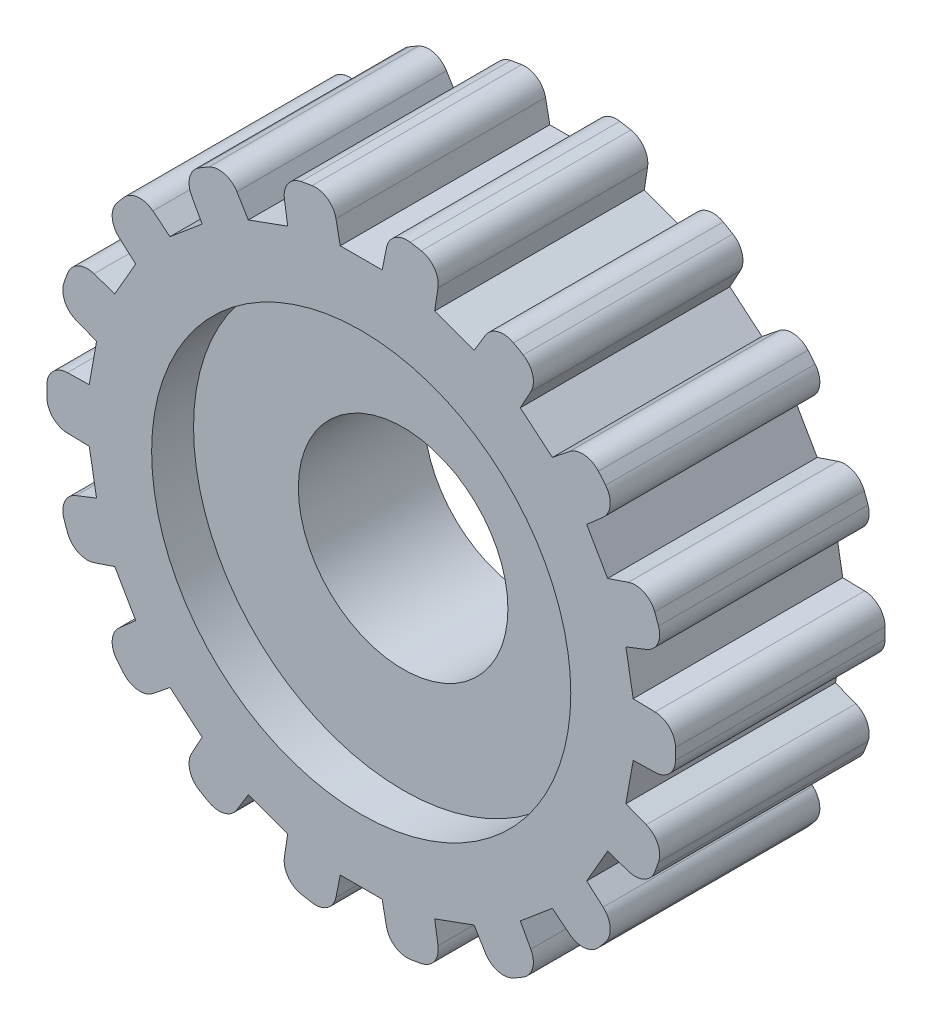
SolidWorks part; units mm, degrees
ref_plane "Front Plane" through (0, 0, 0) normal (0, 0, 1) x (1, 0, 0)
ref_plane "Top Plane" through (0, 0, 0) normal (0, 1, 0) x (1, 0, 0)
ref_plane "Right Plane" through (0, 0, 0) normal (1, 0, 0) x (0, 0, -1)
sketch "Sketch2" plane through (0, 0, 0) normal (0, 0, 1) x (1, 0, 0)
  circle A0 centre (0, 0) radius 50
  circle A1 centre (0, 0) radius 150
  dimension "D1" = 100
  dimension "D2" = 300
extrude "Boss-Extrude1" add sketch "Sketch2" along normal mid plane 100
sketch "Sketch5" plane through (0, 0, 50) normal (0, 0, 1) x (1, 0, 0)
  line L0 (-20, 180) -> (20, 180)
  line L1 (20, 180) -> (10, 130)
  line L2 (10, 130) -> (-10, 130)
  line L3 (-10, 130) -> (-20, 180)
  circle A0 centre (0, 0) radius 150 construction
  point P2 (0, 130)
  point P5 (0, 180)
  point P7 (0, 150)
  point P8 (0, 0)
  dimension "D1" = 20
  dimension "D2" = 40
  dimension "D3" = 50
  dimension "D4" = 20
extrude "Cut-Extrude1" cut sketch "Sketch5" against normal through all
fillet "Fillet1" radius 10 2 edges at (-13.8714, 149.3572, 0) (13.8714, 149.3572, 0)
pattern_circular "CirPattern1" count 18 over 360 about axis through (0, 0, 0) along (0, 0, 1) of "Fillet1", "Cut-Extrude1"
sketch "Sketch6" plane through (0, 0, 50) normal (0, 0, 1) x (1, 0, 0)
  circle A0 centre (0, 0) radius 100
  dimension "D1" = 200
extrude "Cut-Extrude2" cut sketch "Sketch6" against normal blind 20
mirror "Mirror1" about plane through (0, 0, 0) normal (0, 0, 1) of "Cut-Extrude2"
